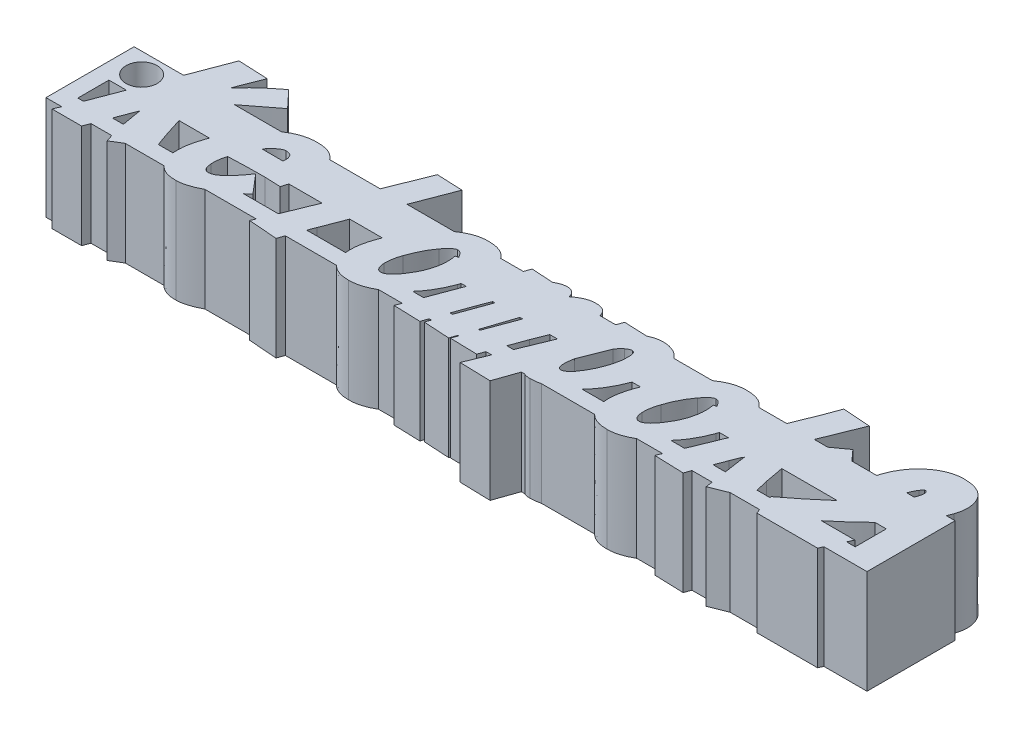
SolidWorks part; units mm, degrees
ref_plane "Front Plane" through (0, 0, 0) normal (0, 0, 1) x (1, 0, 0)
ref_plane "Top Plane" through (0, 0, 0) normal (0, 1, 0) x (1, 0, 0)
ref_plane "Right Plane" through (0, 0, 0) normal (1, 0, 0) x (0, 0, -1)
sketch "Sketch4" plane through (0, 0, 0) normal (0, 1, 0) x (1, 0, 0)
  text T0 "Kelompok2" font "DFPOP1-W9" height 13.0858
  point P1 (0, 0)
extrude "Boss-Extrude2" add sketch "Sketch4" along normal blind 10
sketch "Sketch6" plane through (0, 10, 0) normal (0, 1, 0) x (1, 0, 0)
  line L1 (6.1407, 0.6289) -> (81.138, 0.6289)
  line L2 (6.1407, 0.6289) -> (6.1407, 3.6289)
  line L3 (6.1407, 3.6289) -> (35.1726, 3.6289)
  line L4 (81.138, 0.6289) -> (81.138, 3.6289)
  line L8 (62.4549, 5.609) -> (62.7521, 5.6986) construction
  line L9 (4.5682, -0.8711) -> (83.7762, -0.8711)
  line L10 (4.5682, -0.8711) -> (4.5682, 7.6289)
  line L11 (4.5682, 7.6289) -> (83.7762, 7.6289)
  line L12 (83.7762, -0.8711) -> (83.7762, 7.6289)
  line L13 (52.9448, 5.4722) -> (51.8811, 2.8045) construction
  line L14 (37.5475, 5.609) -> (37.8447, 5.6986) construction
  line L15 (19.2726, 5.2575) -> (21.2893, 5.2575) construction
  line L16 (62.4549, 5.609) -> (62.7521, 5.6986)
  line L17 (52.9448, 5.4722) -> (52.2098, 3.6289)
  line L18 (37.5475, 5.609) -> (37.8447, 5.6986)
  line L19 (19.2726, 5.2575) -> (21.2893, 5.2575)
  line L20 (37.4561, 3.6289) -> (52.2098, 3.6289)
  line L21 (53.9495, 3.6289) -> (60.0801, 3.6289)
  line L22 (62.3635, 3.6289) -> (81.138, 3.6289)
  spline S0 degree 3 poles (2004.4849, -473.4876) (18.7055, -6.9162) (61.0809, -6.0095) (62.5298, 4.4889) (62.6896, 14.5288) (20.146, 20.8649) (2053.0519, 197.7756) knots -13.18947 -13.18947 -13.18947 -13.18947 0.256764 0.507287 0.753246 13.457519 13.457519 13.457519 13.457519 only from (62.2875, 3.3659) to (62.4549, 5.609) construction
  spline S1 degree 3 poles (-1536.2854, -1195.4899) (91.54, 19.6615) (36.1796, -13.7219) (86.4376, 31.4898) (-1547.5215, -1180.4134) knots -30.629046 -30.629046 -30.629046 -30.629046 0.466248 33.041938 33.041938 33.041938 33.041938 only from (62.7521, 5.6986) to (62.5776, 5.9368) construction
  spline S2 degree 3 poles (1590.5787, 1296.3265) (41.7246, -21.4066) (65.3263, 3.7052) (62.3509, 6.1885) (59.3313, 7.5706) (48.6088, -25.7118) (489.7715, 1959.8609) knots -16.91729 -16.91729 -16.91729 -16.91729 0.277437 0.527579 0.76171 15.333295 15.333295 15.333295 15.333295 only from (62.5776, 5.9368) to (62.0516, 6.267) construction
  spline S3 degree 3 poles (-374.3056, 1957.9632) (72.6014, -19.7395) (64.0747, 7.2064) (61.8519, 6.2145) (61.7428, 6.1495) (61.6235, 6.0617) (61.5005, 5.9438) (61.3652, 5.8052) (55.7543, -0.8208) (65.8691, -19.6367) (-1531.0421, 1215.6941) knots -5.286709 -5.286709 -5.286709 -5.286709 0.071393 0.15535 0.252198 0.365139 0.496199 0.645155 0.812557 20.532334 20.532334 20.532334 20.532334 only from (62.0516, 6.267) to (61.0798, 5.4533) construction
  spline S4 degree 3 poles (-1600.6214, 1118.1597) (103.7383, 4.0413) (66.1002, 14.6795) (60.4224, 4.4102) (54.3121, -8.7205) (82.7094, -35.7125) (-1806.8514, 720.5337) knots -12.730063 -12.730063 -12.730063 -12.730063 0.225973 0.466605 0.724413 16.848048 16.848048 16.848048 16.848048 only from (61.0798, 5.4533) to (59.8958, 3.1371) construction
  spline S5 degree 3 poles (1710.3501, -1117.2929) (12.545, 1.6616) (47.7368, -7.491) (53.5542, 2.7077) (58.9198, 14.0148) (32.3025, 38.2886) (1916.6005, -724.39) knots -14.836121 -14.836121 -14.836121 -14.836121 0.24429 0.491414 0.743315 16.855909 16.855909 16.855909 16.855909 only from (52.9566, 1.7691) to (53.9991, 3.7621) construction
  spline S6 degree 3 poles (1971.2216, -565.2442) (16.9876, -7.4294) (51.8619, -5.9924) (54.2529, 4.6865) (55.6033, 13.7248) (22.5424, 25.259) (2050.1508, -122.2076) knots -17.142115 -17.142115 -17.142115 -17.142115 0.272219 0.528497 0.770451 15.216364 15.216364 15.216364 15.216364 only from (53.9991, 3.7621) to (54.3294, 5.5547) construction
  spline S7 degree 3 poles (-371.7627, 1960.4071) (65.0876, -19.5814) (56.3373, 7.2927) (53.7364, 6.2224) (49.2307, 3.8183) (58.2299, -21.2793) (-979.2217, 1718.752) knots -13.578929 -13.578929 -13.578929 -13.578929 0.182996 0.406157 0.680259 26.376586 26.376586 26.376586 26.376586 only from (53.9756, 6.2835) to (53.4496, 6.0453) construction
  spline S8 degree 3 poles (2054.159, -16.2285) (35.1585, -6.0346) (54.7788, -0.1267) (54.315, 5.8667) (54.2857, 5.9929) (54.2501, 6.0984) (54.2004, 6.1818) (54.1372, 6.2419) (52.1186, 7.1548) (44.2981, -20.2834) (450.7299, 1966.5032) knots -19.45555 -19.45555 -19.45555 -19.45555 0.188466 0.354056 0.496244 0.618749 0.723314 0.815897 0.904899 7.930481 7.930481 7.930481 7.930481 only from (54.3294, 5.5547) to (53.9756, 6.2835) construction
  spline S9 degree 3 poles (-1309.2263, 1469.8528) (78.3257, -6.7861) (56.464, 9.3902) (53.1823, 5.7909) (49.692, 1.7126) (68.6224, -19.0062) (-1559.5761, 1188.499) knots -18.279545 -18.279545 -18.279545 -18.279545 0.235416 0.476799 0.732258 21.197022 21.197022 21.197022 21.197022 only from (53.4496, 6.0453) to (52.9448, 5.4722) construction
  spline S10 degree 3 poles (1979.5774, -473.4876) (-6.202, -6.9162) (36.1734, -6.0095) (37.6223, 4.4889) (37.7821, 14.5288) (-4.7615, 20.8649) (2028.1445, 197.7756) knots -13.18947 -13.18947 -13.18947 -13.18947 0.256764 0.507287 0.753246 13.457519 13.457519 13.457519 13.457519 only from (37.38, 3.3659) to (37.5475, 5.609) construction
  spline S11 degree 3 poles (-1561.1928, -1195.4899) (66.6325, 19.6615) (11.2722, -13.7219) (61.5301, 31.4898) (-1572.4289, -1180.4134) knots -30.629046 -30.629046 -30.629046 -30.629046 0.466248 33.041938 33.041938 33.041938 33.041938 only from (37.8447, 5.6986) to (37.6702, 5.9368) construction
  spline S12 degree 3 poles (1565.6713, 1296.3265) (16.8172, -21.4066) (40.4189, 3.7052) (37.4435, 6.1885) (34.4239, 7.5706) (23.7014, -25.7118) (464.864, 1959.8609) knots -16.91729 -16.91729 -16.91729 -16.91729 0.277437 0.527579 0.76171 15.333295 15.333295 15.333295 15.333295 only from (37.6702, 5.9368) to (37.1442, 6.267) construction
  spline S13 degree 3 poles (-399.213, 1957.9632) (47.694, -19.7395) (39.1673, 7.2064) (36.9444, 6.2145) (36.8353, 6.1495) (36.7161, 6.0617) (36.5931, 5.9438) (36.4577, 5.8052) (30.8468, -0.8208) (40.9616, -19.6367) (-1555.9495, 1215.6941) knots -5.286709 -5.286709 -5.286709 -5.286709 0.071393 0.15535 0.252198 0.365139 0.496199 0.645155 0.812557 20.532334 20.532334 20.532334 20.532334 only from (37.1442, 6.267) to (36.1724, 5.4533) construction
  spline S14 degree 3 poles (-1625.5289, 1118.1597) (78.8309, 4.0413) (41.1928, 14.6795) (35.5149, 4.4102) (29.4047, -8.7205) (57.802, -35.7125) (-1831.7588, 720.5337) knots -12.730063 -12.730063 -12.730063 -12.730063 0.225973 0.466605 0.724413 16.848048 16.848048 16.848048 16.848048 only from (36.1724, 5.4533) to (34.9884, 3.1371) construction
  spline S15 degree 3 poles (1564.0746, -1264.9385) (15.779, 27.9333) (31.6667, -3.9109) (0.306, 3.9971) (1536.7583, -1297.3874) knots -68.897847 -68.897847 -68.897847 -68.897847 0.585956 62.365757 62.365757 62.365757 62.365757 only from (19.4802, 5.5052) to (19.2726, 5.2575) construction
  spline S16 degree 3 poles (2008.6649, -218.3855) (-9.69, -0.0361) (21.3898, 1.1147) (21.3206, 5.628) (20.4856, 9.909) (-10.1519, 4.2446) (1915.5546, 647.1916) knots -17.5005 -17.5005 -17.5005 -17.5005 0.258804 0.505168 0.749864 17.881942 17.881942 17.881942 17.881942 only from (21.2893, 5.2575) to (21.2138, 5.9769) construction
  spline S17 degree 3 poles (1480.7198, 1373.2388) (-2.1267, -23.9458) (23.6682, 4.5446) (20.9817, 6.2035) (16.8001, 7.4905) (7.0612, -26.7813) (320.0674, 1983.6298) knots -12.25481 -12.25481 -12.25481 -12.25481 0.222813 0.449951 0.70372 18.528776 18.528776 18.528776 18.528776 only from (21.2138, 5.9769) to (20.6029, 6.267) construction
  spline S18 degree 3 poles (-299.3117, 1980.4268) (30.7988, -19.0811) (23.3397, 7.1529) (20.3589, 6.2206) (20.2277, 6.1612) (20.0923, 6.0739) (19.9466, 5.9678) (19.7977, 5.8341) (14.6397, 0.8936) (27.1723, -21.0791) (-1431.8072, 1381.5368) knots -6.409227 -6.409227 -6.409227 -6.409227 0.083543 0.175339 0.277812 0.393598 0.52217 0.666413 0.824746 15.924522 15.924522 15.924522 15.924522 only from (20.6029, 6.267) to (19.4802, 5.5052) construction
  spline S19 degree 3 poles (62.3635, 3.6289) (62.3911, 3.7285) (62.464, 4.0124) (62.5298, 4.4889) (62.5388, 5.0542) (62.4829, 5.4238) (62.4549, 5.609) knots 0.120366 0.120366 0.120366 0.120366 0.256764 0.507287 0.753246 1 1 1 1
  spline S20 degree 3 poles (62.7521, 5.6986) (62.7188, 5.731) (62.6473, 5.8005) (62.6018, 5.8894) (62.5776, 5.9368) knots 0 0 0 0 0.466248 1 1 1 1
  spline S21 degree 3 poles (62.5776, 5.9368) (62.5437, 5.9867) (62.4791, 6.0815) (62.3509, 6.1885) (62.206, 6.2548) (62.1034, 6.2629) (62.0516, 6.267) knots 0 0 0 0 0.277437 0.527579 0.76171 1 1 1 1
  spline S22 degree 3 poles (62.0516, 6.267) (62.0206, 6.2647) (61.9531, 6.2596) (61.8519, 6.2145) (61.7428, 6.1495) (61.6235, 6.0617) (61.5005, 5.9438) (61.3652, 5.8052) (61.2241, 5.6386) (61.1297, 5.5173) (61.0798, 5.4533) knots 0 0 0 0 0.071393 0.15535 0.252198 0.365139 0.496199 0.645155 0.812557 1 1 1 1
  spline S23 degree 3 poles (61.0798, 5.4533) (60.9651, 5.2933) (60.7281, 4.9631) (60.4224, 4.4102) (60.2117, 3.9576) (60.1038, 3.6893) (60.0801, 3.6289) knots 0 0 0 0 0.225973 0.466605 0.724413 0.798917 0.798917 0.798917 0.798917
  spline S24 degree 3 poles (53.9495, 3.6289) (53.9661, 3.6733) (53.9826, 3.7177) (53.9991, 3.7621) knots 0.937053 0.937053 0.937053 0.937053 1 1 1 1
  spline S25 degree 3 poles (53.9991, 3.7621) (54.0505, 3.9202) (54.1501, 4.2272) (54.2529, 4.6865) (54.3187, 5.1266) (54.3259, 5.4145) (54.3294, 5.5547) knots 0 0 0 0 0.272219 0.528497 0.770451 1 1 1 1
  spline S26 degree 3 poles (53.9756, 6.2835) (53.9398, 6.2804) (53.8605, 6.2735) (53.7364, 6.2224) (53.5959, 6.1474) (53.5008, 6.0811) (53.4496, 6.0453) knots 0 0 0 0 0.182996 0.406157 0.680259 1 1 1 1
  spline S27 degree 3 poles (54.3294, 5.5547) (54.3284, 5.6113) (54.3266, 5.7177) (54.315, 5.8667) (54.2857, 5.9929) (54.2501, 6.0984) (54.2004, 6.1818) (54.1372, 6.2419) (54.0597, 6.2769) (54.0042, 6.2813) (53.9756, 6.2835) knots 0 0 0 0 0.188466 0.354056 0.496244 0.618749 0.723314 0.815897 0.904899 1 1 1 1
  spline S28 degree 3 poles (53.4496, 6.0453) (53.403, 6.007) (53.3087, 5.9295) (53.1823, 5.7909) (53.055, 5.6421) (52.9821, 5.5297) (52.9448, 5.4722) knots 0 0 0 0 0.235416 0.476799 0.732258 1 1 1 1
  spline S29 degree 3 poles (37.4561, 3.6289) (37.4837, 3.7285) (37.5566, 4.0124) (37.6223, 4.4889) (37.6313, 5.0542) (37.5755, 5.4238) (37.5475, 5.609) knots 0.120366 0.120366 0.120366 0.120366 0.256764 0.507287 0.753246 1 1 1 1
  spline S30 degree 3 poles (37.8447, 5.6986) (37.8114, 5.731) (37.7399, 5.8005) (37.6944, 5.8894) (37.6702, 5.9368) knots 0 0 0 0 0.466248 1 1 1 1
  spline S31 degree 3 poles (37.6702, 5.9368) (37.6362, 5.9867) (37.5717, 6.0815) (37.4435, 6.1885) (37.2986, 6.2548) (37.1959, 6.2629) (37.1442, 6.267) knots 0 0 0 0 0.277437 0.527579 0.76171 1 1 1 1
  spline S32 degree 3 poles (37.1442, 6.267) (37.1131, 6.2647) (37.0456, 6.2596) (36.9444, 6.2145) (36.8353, 6.1495) (36.7161, 6.0617) (36.5931, 5.9438) (36.4577, 5.8052) (36.3166, 5.6386) (36.2223, 5.5173) (36.1724, 5.4533) knots 0 0 0 0 0.071393 0.15535 0.252198 0.365139 0.496199 0.645155 0.812557 1 1 1 1
  spline S33 degree 3 poles (36.1724, 5.4533) (36.0576, 5.2933) (35.8206, 4.9631) (35.5149, 4.4102) (35.3043, 3.9576) (35.1963, 3.6893) (35.1726, 3.6289) knots 0 0 0 0 0.225973 0.466605 0.724413 0.798917 0.798917 0.798917 0.798917
  spline S34 degree 3 poles (19.4802, 5.5052) (19.4404, 5.4562) (19.3725, 5.3725) (19.3019, 5.2912) (19.2726, 5.2575) knots 0 0 0 0 0.585956 1 1 1 1
  spline S35 degree 3 poles (21.2893, 5.2575) (21.3008, 5.3202) (21.3234, 5.4425) (21.3206, 5.628) (21.2855, 5.808) (21.2379, 5.9202) (21.2138, 5.9769) knots 0 0 0 0 0.258804 0.505168 0.749864 1 1 1 1
  spline S36 degree 3 poles (21.2138, 5.9769) (21.1853, 6.0221) (21.1276, 6.1134) (20.9817, 6.2035) (20.8042, 6.2581) (20.6734, 6.2639) (20.6029, 6.267) knots 0 0 0 0 0.222813 0.449951 0.70372 1 1 1 1
  spline S37 degree 3 poles (20.6029, 6.267) (20.5641, 6.2645) (20.4828, 6.2594) (20.3589, 6.2206) (20.2277, 6.1612) (20.0923, 6.0739) (19.9466, 5.9678) (19.7977, 5.8341) (19.6377, 5.6808) (19.5344, 5.5657) (19.4802, 5.5052) knots 0 0 0 0 0.083543 0.175339 0.277812 0.393598 0.52217 0.666413 0.824746 1 1 1 1
  dimension "D1" = 3
  dimension "D2" = 4
  dimension "D3" = 1.5
extrude "Boss-Extrude10" add sketch "Sketch6" against normal up to surface (10 mm away)
sketch "Sketch9" plane through (0, 10, 0) normal (0, 1, 0) x (1, 0, 0)
  circle A0 centre (7.2578, 5.6653) radius 1.5
  point P2 (7.2578, 5.6653)
  dimension "D1" = 3
extrude "Cut-Extrude3" cut sketch "Sketch9" against normal blind 25
